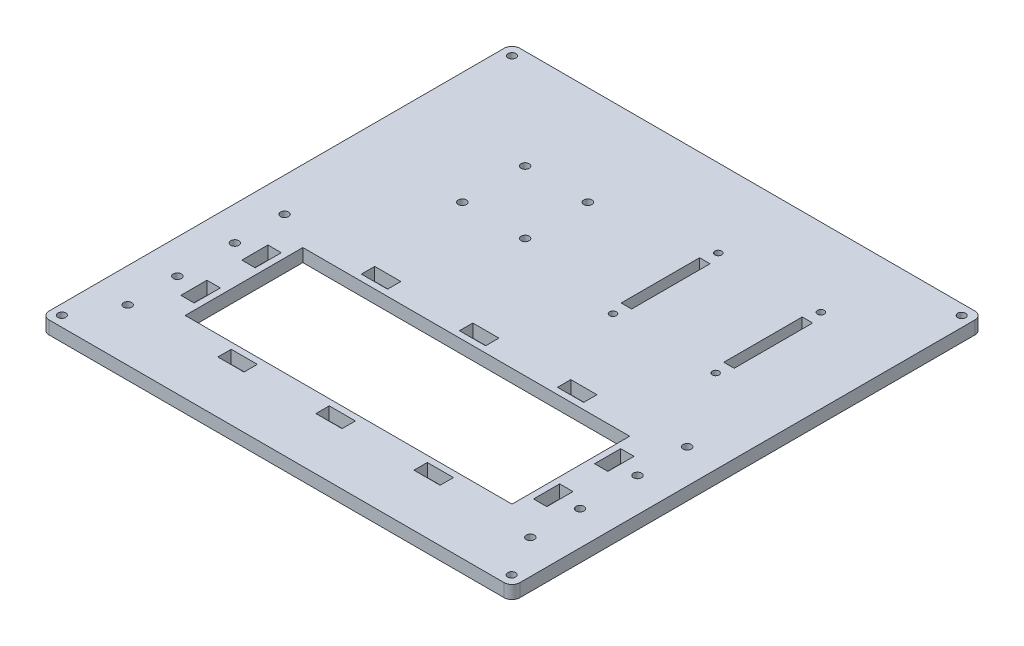
SolidWorks part; units mm, degrees
ref_plane "Front Plane" through (0, 0, 0) normal (0, 0, 1) x (1, 0, 0)
ref_plane "Top Plane" through (0, 0, 0) normal (0, 1, 0) x (1, 0, 0)
ref_plane "Right Plane" through (0, 0, 0) normal (1, 0, 0) x (0, 0, -1)
sketch "Sketch1" plane through (0, 0, 0) normal (0, 1, 0) x (1, 0, 0)
  line L1 (-90, -90) -> (90, -90)
  line L2 (-90, -90) -> (-90, 90)
  line L3 (-90, 90) -> (90, 90)
  line L4 (90, -90) -> (90, 90)
  line L5 (-90, -90) -> (90, 90) construction
  line L6 (-90, 90) -> (90, -90) construction
  circle A0 centre (-86, 86) radius 1.5
  circle A1 centre (86, 86) radius 1.5
  circle A2 centre (85.8407, -86) radius 1.5
  circle A3 centre (-86.1593, -86) radius 1.5
  point P0 (0, 0)
  dimension "D7" = 3
  dimension "D8" = 4
  dimension "D1" = 180
  dimension "D2" = 180
  dimension "D9" = 2
  dimension "D16" = 4
  dimension "D18" = 4
  dimension "D19" = 4
  dimension "D10" = 2
extrude "Boss-Extrude1" add sketch "Sketch1" along normal blind 5
sketch "Sketch3" plane through (0, 5, 0) normal (0, 1, 0) x (1, 0, 0)
  line L0 (90, -90) -> (90, 90) construction
  line L1 (20, 85) -> (80, 85)
  line L2 (20, 85) -> (20, 5)
  line L3 (20, 5) -> (80, 5)
  line L4 (80, 85) -> (80, 5)
  line L5 (-90, 90) -> (90, 90) construction
  dimension "D1" = 80
  dimension "D2" = 60
  dimension "D3" = 10
  dimension "D4" = 5
extrude "Boss-Extrude2" [suppressed] add sketch "Sketch3" along normal blind 5
sketch "Sketch4" plane through (0, 5, 0) normal (0, 1, 0) x (1, 0, 0)
  line L0 (-90, -90) -> (90, -90) construction
  line L5 (70, -33.3333) -> (70, -46.6667) construction
  line L6 (-75.9979, -60) -> (-90, -60) construction
  line L7 (-32.5, -10) -> (-5, -10)
  line L8 (75.9979, -60) -> (90, -60) construction
  line L9 (-42.5, -10) -> (-32.5, -10)
  line L10 (-42.5, -10) -> (-42.5, -15.1)
  line L11 (-42.5, -15.1) -> (-32.5, -15.1)
  line L12 (-32.5, -10) -> (-32.5, -15.1)
  line L13 (-5, -10) -> (5, -10)
  line L14 (-5, -10) -> (-5, -15.1)
  line L15 (-5, -15.1) -> (5, -15.1)
  line L16 (5, -10) -> (5, -15.1)
  line L17 (32.5, -10) -> (42.5, -10)
  line L18 (32.5, -10) -> (32.5, -15.1)
  line L19 (32.5, -15.1) -> (42.5, -15.1)
  line L20 (42.5, -10) -> (42.5, -15.1)
  line L21 (90, -90) -> (90, 90) construction
  line L22 (-42.5, -64.9) -> (-42.5, -70)
  line L23 (-70, -23.3333) -> (-64.9, -23.3333)
  line L24 (-70, -23.3333) -> (-70, -33.3333)
  line L25 (-70, -33.3333) -> (-64.9, -33.3333)
  line L26 (-64.9, -23.3333) -> (-64.9, -33.3333)
  line L31 (-70, -46.6667) -> (-64.9, -46.6667)
  line L32 (-70, -46.6667) -> (-70, -56.6667)
  line L33 (-70, -56.6667) -> (-64.9, -56.6667)
  line L34 (-64.9, -46.6667) -> (-64.9, -56.6667)
  line L35 (-42.5, -64.9) -> (-32.5, -64.9)
  line L36 (-32.5, -64.9) -> (-32.5, -70)
  line L37 (-42.5, -70) -> (-32.5, -70)
  line L38 (-5, -64.9) -> (-5, -70)
  line L39 (-5, -64.9) -> (5, -64.9)
  line L40 (5, -64.9) -> (5, -70)
  line L41 (-5, -70) -> (5, -70)
  line L42 (32.5, -64.9) -> (32.5, -70)
  line L43 (32.5, -64.9) -> (42.5, -64.9)
  line L44 (42.5, -64.9) -> (42.5, -70)
  line L45 (32.5, -70) -> (42.5, -70)
  line L46 (64.9, -23.3333) -> (64.9, -33.3333)
  line L47 (64.9, -23.3333) -> (70, -23.3333)
  line L48 (70, -23.3333) -> (70, -33.3333)
  line L49 (64.9, -33.3333) -> (70, -33.3333)
  line L54 (64.9, -46.6667) -> (64.9, -56.6667)
  line L55 (64.9, -46.6667) -> (70, -46.6667)
  line L56 (70, -46.6667) -> (70, -56.6667)
  line L57 (64.9, -56.6667) -> (70, -56.6667)
  line L58 (5, -10) -> (32.5, -10)
  line L59 (-70, -33.3333) -> (-70, -46.6667) construction
  line L60 (-75.9979, -60) -> (-62.5, -60) construction
  line L61 (-32.5, -67.45) -> (-17.5, -77.45) construction
  line L62 (5, -67.45) -> (20, -77.45) construction
  line L63 (-62.5, -17.5) -> (62.5, -17.5)
  line L64 (-62.5, -17.5) -> (-62.5, -62.5)
  line L65 (42.5, -10) -> (70, -10)
  line L66 (70, -10) -> (70, -23.3333)
  line L67 (-62.5, -62.5) -> (62.5, -62.5)
  line L68 (62.5, -17.5) -> (62.5, -62.5)
  line L69 (70, -56.6667) -> (70, -70)
  line L70 (70, -70) -> (42.5, -70)
  line L71 (32.5, -70) -> (5, -70)
  line L72 (-5, -70) -> (-32.5, -70)
  line L73 (-42.5, -70) -> (-70, -70)
  line L74 (-70, -70) -> (-70, -56.6667)
  line L75 (75.9979, -60) -> (62.5, -60) construction
  line L76 (0, -15.1) -> (0, -17.5) construction
  line L77 (-70, -23.3333) -> (-70, -10)
  line L78 (-70, -10) -> (-42.5, -10)
  line L79 (-90, -90) -> (-90, 90) construction
  line L84 (0, -64.9) -> (0, -62.5) construction
  dimension "D3" = 140
  dimension "D4" = 60
  dimension "D5" = 10
  dimension "D6" = 10
  dimension "D7" = 10
  dimension "D8" = 20
  dimension "D9" = 45
  dimension "D10" = 125
  dimension "D11" = 5.1
  dimension "D12" = 5.1
  dimension "D13" = 5.1
  dimension "D14" = 10
  dimension "D16" = 10
  dimension "D20" = 5.1
  dimension "D21" = 2
  dimension "D22" = 2
extrude "Cut-Extrude1" cut sketch "Sketch4" against normal up to next
sketch "Sketch5" plane through (0, 5, 0) normal (0, 1, 0) x (1, 0, 0)
  line L0 (-90, 90) -> (90, 90) construction
  line L1 (-50, 55) -> (-20, 55)
  line L2 (-50, 55) -> (-50, 25)
  line L3 (-50, 25) -> (-20, 25)
  line L4 (-20, 55) -> (-20, 25)
  line L5 (-90, -90) -> (-90, 90) construction
  circle A0 centre (-47, 52) radius 1.55
  circle A1 centre (-23, 52) radius 1.55
  circle A2 centre (-23, 28) radius 1.55
  circle A3 centre (-47, 28) radius 1.55
  dimension "D3" = 3.1
  dimension "D1" = 30
  dimension "D2" = 30
  dimension "D4" = 3
  dimension "D5" = 3
  dimension "D8" = 35
  dimension "D9" = 40
  dimension "D6" = 2
  dimension "D7" = 2
extrude "Cut-Extrude3" cut sketch "Sketch5" against normal through all
sketch "Sketch6" plane through (0, 5, 0) normal (0, 1, 0) x (1, 0, 0)
  line L0 (-90, 90) -> (90, 90) construction
  line L1 (16.75, 61.625) -> (60, 61.625)
  line L2 (16.75, 61.625) -> (16.75, 18.375)
  line L3 (16.75, 18.375) -> (60, 18.375)
  line L4 (60, 61.625) -> (60, 18.375)
  line L5 (90, -90) -> (90, 90) construction
  line L6 (20.75, 55) -> (20.75, 25)
  line L7 (60, 55) -> (56, 55)
  line L8 (60, 55) -> (60, 25)
  line L9 (60, 25) -> (56, 25)
  line L10 (56, 55) -> (56, 25)
  line L11 (20.75, 55) -> (16.75, 55)
  line L12 (16.75, 55) -> (16.75, 25)
  line L13 (20.75, 25) -> (16.75, 25)
  circle A0 centre (58, 60.125) radius 1.3
  circle A1 centre (18.75, 60.125) radius 1.3
  circle A2 centre (18.75, 19.875) radius 1.3
  circle A3 centre (58, 19.875) radius 1.3
  dimension "D5" = 2.6
  dimension "D1" = 43.25
  dimension "D2" = 43.25
  dimension "D3" = 28.375
  dimension "D4" = 30
  dimension "D6" = 2
  dimension "D7" = 1.5
  dimension "D10" = 30
  dimension "D11" = 6.625
  dimension "D12" = 4
  dimension "D8" = 2
  dimension "D9" = 2
  dimension "D13" = 2
extrude "Cut-Extrude5" cut sketch "Sketch6" against normal blind 10 contours L13 L6 L11 L2 | L7 L10 L9 L4 | A0 | A1 | A2 | A3
sketch "Sketch7" plane through (0, 5, 0) normal (0, 1, 0) x (1, 0, 0)
  line L1 (-80, -7) -> (-55, -7)
  line L2 (-80, -7) -> (-80, -32)
  line L3 (-80, -32) -> (-55, -32)
  line L4 (-55, -7) -> (-55, -32)
  line L18 (-70, -23.3333) -> (-70, -33.3333) construction
  line L21 (70, -23.3333) -> (70, -33.3333) construction
  circle A0 centre (-77, -10) radius 1.55
  circle A1 centre (-77, -29) radius 1.55
  circle A2 centre (-77, -51) radius 1.55
  circle A3 centre (-77, -70) radius 1.55
  circle A4 centre (77, -29) radius 1.55
  circle A5 centre (77, -10) radius 1.55
  circle A6 centre (77, -70) radius 1.55
  circle A7 centre (77, -51) radius 1.55
  point P6 (0, 0)
  point P7 (0, 0)
  point P11 (0, 0)
  point P14 (0, 0)
  point P15 (0, 0)
  point P16 (0, 0)
  point P17 (0, 0)
  point P20 (0, 0)
  point P21 (0, 0)
  point P22 (0, 0)
  point P23 (0, 0)
  point P36 (0, 0)
  point P37 (0, 0)
  point P39 (0, 0)
  dimension "D3" = 3.1
  dimension "D8" = 7
  dimension "D9" = 19
  dimension "D1" = 25
  dimension "D2" = 25
  dimension "D4" = 3
  dimension "D5" = 3
  dimension "D7" = 10
  dimension "D6" = 2
extrude "Cut-Extrude6" cut sketch "Sketch7" against normal through all contours A1 | A0 | A2 | A3 | A6 | A7 | A4 | A5
fillet "Fillet1" radius 3 4 edges at (90, 2.5, 90) (-90, 2.5, 90) (90, 2.5, -90) (-90, 2.5, -90)
